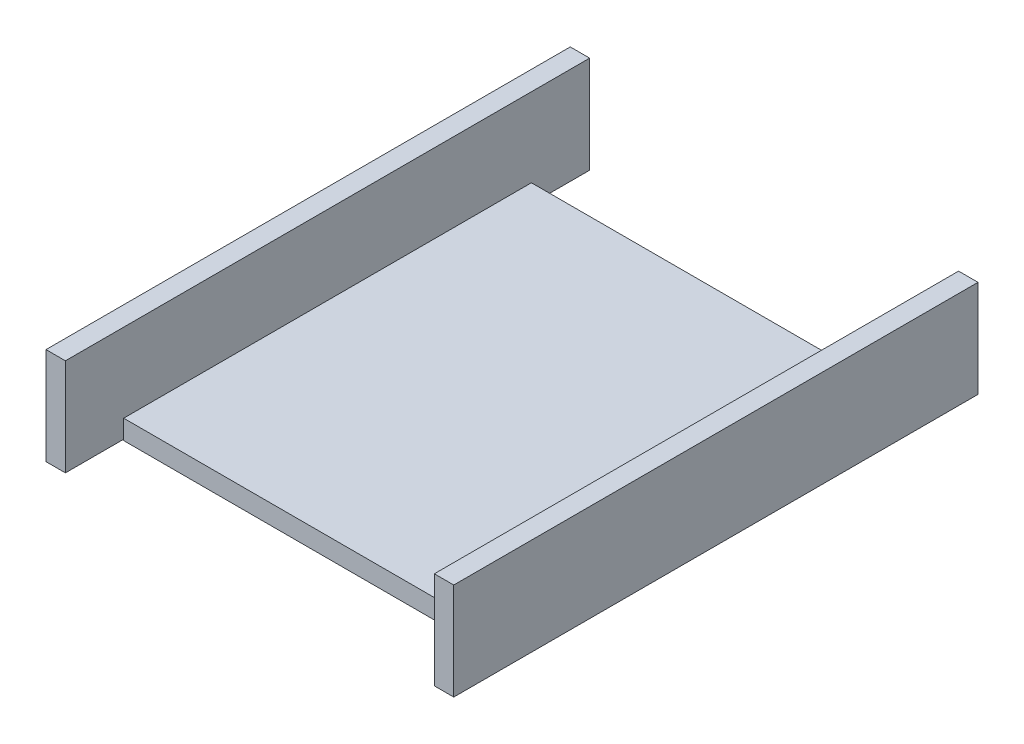
SolidWorks part; units mm, degrees
ref_plane "前视基准面" through (0, 0, 0) normal (0, 0, 1) x (1, 0, 0)
ref_plane "上视基准面" through (0, 0, 0) normal (0, 1, 0) x (1, 0, 0)
ref_plane "右视基准面" through (0, 0, 0) normal (1, 0, 0) x (0, 0, -1)
sketch "草图1" plane through (0, 0, 0) normal (1, 0, 0) x (0, 0, -1)
  line L1 (-67.5, 12.5) -> (67.5, 12.5)
  line L2 (-67.5, 12.5) -> (-67.5, -12.5)
  line L3 (-67.5, -12.5) -> (67.5, -12.5)
  line L4 (67.5, 12.5) -> (67.5, -12.5)
  line L5 (-67.5, 12.5) -> (67.5, -12.5) construction
  line L6 (-67.5, -12.5) -> (67.5, 12.5) construction
  point P0 (0, 0)
  dimension "D1" = 135
  dimension "D2" = 25
extrude "凸台-拉伸1" add sketch "草图1" along normal blind 5
sketch "草图3" plane through (5, 0, 0) normal (1, 0, 0) x (0, 0, -1)
  line L0 (-67.5, 12.5) -> (-67.5, -12.5) construction
  line L1 (52.5, -12.8009) -> (-52.5, -12.8009)
  line L2 (52.5, -12.8009) -> (52.5, -7.8009)
  line L3 (52.5, -7.8009) -> (-52.5, -7.8009)
  line L4 (-52.5, -12.8009) -> (-52.5, -7.8009)
  line L5 (52.5, -12.8009) -> (-52.5, -7.8009) construction
  line L6 (52.5, -7.8009) -> (-52.5, -12.8009) construction
  point P0 (0, -10.3009)
  dimension "D1" = 15
  dimension "D2" = 105
  dimension "D3" = 5
extrude "凸台-拉伸2" add sketch "草图3" along normal blind 95
sketch "草图4" plane through (100, 0, 0) normal (1, 0, 0) x (0, 0, -1)
  line L0 (-67.5, -12.5) -> (-52.5, -12.5) construction
  line L1 (67.5, 12.5) -> (-67.5, 12.5)
  line L2 (67.5, 12.5) -> (67.5, -12.5)
  line L3 (67.5, -12.5) -> (-67.5, -12.5)
  line L4 (-67.5, 12.5) -> (-67.5, -12.5)
  line L5 (67.5, 12.5) -> (-67.5, -12.5) construction
  line L6 (67.5, -12.5) -> (-67.5, 12.5) construction
  point P1 (0, 0)
  dimension "D1" = 135
extrude "凸台-拉伸3" add sketch "草图4" along normal blind 5
